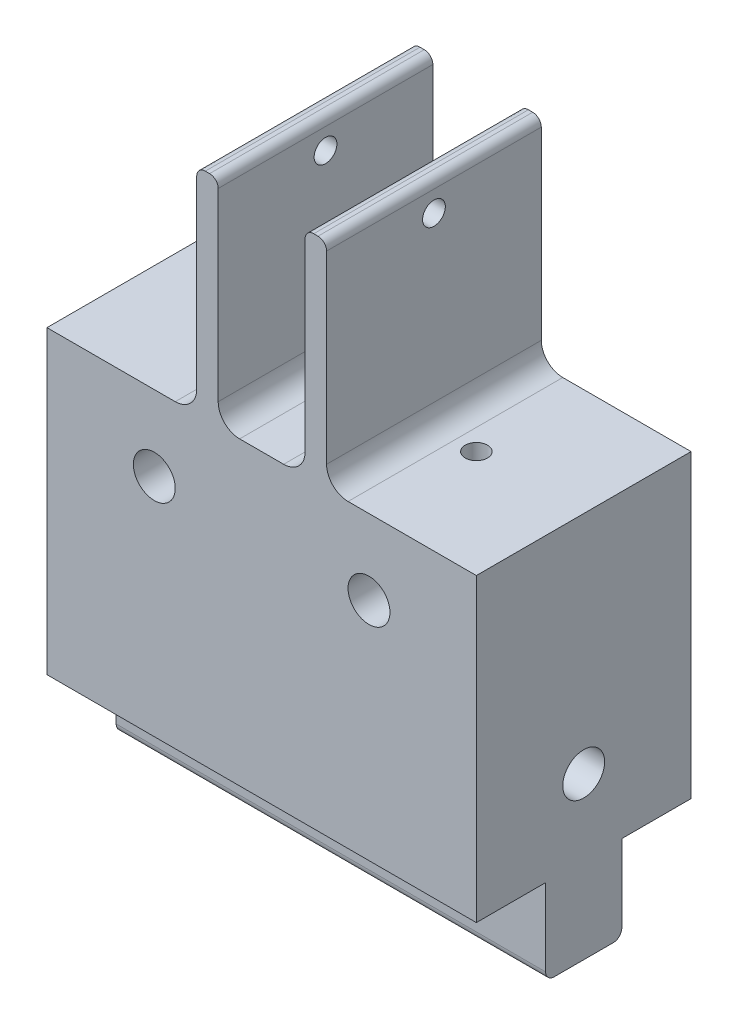
SolidWorks part; units mm, degrees
ref_plane "Front Plane" through (0, 0, 0) normal (0, 0, 1) x (1, 0, 0)
ref_plane "Top Plane" through (0, 0, 0) normal (0, 1, 0) x (1, 0, 0)
ref_plane "Right Plane" through (0, 0, 0) normal (1, 0, 0) x (0, 0, -1)
sketch "Sketch1" plane through (0, 0, 0) normal (0, 0, 1) x (1, 0, 0)
  line L1 (-50, -35) -> (50, -35)
  line L2 (-50, -35) -> (-50, 35)
  line L3 (-50, 35) -> (50, 35)
  line L4 (50, -35) -> (50, 35)
  line L5 (-50, -35) -> (50, 35) construction
  line L6 (-50, 35) -> (50, -35) construction
  point P0 (0, 0)
  dimension "D1" = 70
  dimension "D2" = 100
extrude "Boss-Extrude1" add sketch "Sketch1" along normal mid plane 50
sketch "Sketch2" plane through (0, 0, 25) normal (0, 0, 1) x (1, 0, 0)
  line L0 (0, 0) -> (50, 35) construction
  line L1 (0, 0) -> (-50, 35) construction
  circle A0 centre (25, 17.5) radius 4.875
  circle A1 centre (-25, 17.5) radius 4.875
  dimension "D1" = 9.75
extrude "Cut-Extrude1" cut sketch "Sketch2" against normal through all both and the other way through all
sketch "Sketch3" plane through (-50, 0, 0) normal (-1, 0, 0) x (0, 0, 1)
  line L0 (0, 0) -> (0, -35) construction
  line L1 (25, -35) -> (-25, -35) construction
  circle A0 centre (0, -17.5) radius 4.875
  dimension "D1" = 9.75
extrude "Cut-Extrude2" cut sketch "Sketch3" against normal through all both
sketch "Sketch4" plane through (0, 35, 0) normal (0, 1, 0) x (1, 0, 0)
  line L0 (-50, 0) -> (0, 0) construction
  line L1 (-50, -25) -> (-50, 25) construction
  line L3 (0, 0) -> (50, 0) construction
  line L4 (50, -25) -> (50, 25) construction
  circle A0 centre (-25, 0) radius 2.6
  circle A1 centre (25, 0) radius 2.6
  point P5 (-25, 0)
  dimension "D1" = 5.2
extrude "Cut-Extrude4" cut sketch "Sketch4" against normal blind 20
sketch "Sketch5" plane through (0, -35, 0) normal (0, -1, 0) x (1, 0, 0)
  line L0 (50, 25) -> (50, -25) construction
  line L1 (-50, -8.875) -> (50, -8.875)
  line L2 (-50, -8.875) -> (-50, 8.875)
  line L3 (-50, 8.875) -> (50, 8.875)
  line L4 (50, -8.875) -> (50, 8.875)
  line L5 (-50, -8.875) -> (50, 8.875) construction
  line L6 (-50, 8.875) -> (50, -8.875) construction
  point P0 (0, 0)
  dimension "D1" = 17.75
extrude "Boss-Extrude2" add sketch "Sketch5" along normal blind 20
fillet "Fillet1" radius 2 2 edges at (0, -55, -8.875) (0, -55, 8.875)
sketch "Sketch6" plane through (0, 35, 0) normal (0, 1, 0) x (1, 0, 0)
  line L0 (50, 25) -> (-50, 25) construction
  line L1 (-15.125, 25) -> (-10.125, 25)
  line L2 (-15.125, 25) -> (-15.125, -25)
  line L3 (-15.125, -25) -> (-10.125, -25)
  line L4 (-10.125, 25) -> (-10.125, -25)
  line L5 (50, -25) -> (-50, -25) construction
  line L6 (-10.125, 0) -> (10.125, 0) construction
  line L7 (15.125, 25) -> (10.125, 25)
  line L8 (15.125, 25) -> (15.125, -25)
  line L9 (15.125, -25) -> (10.125, -25)
  line L10 (10.125, 25) -> (10.125, -25)
  point P16 (0, 0)
  dimension "D1" = 20.25
  dimension "D2" = 5
extrude "Boss-Extrude3" add sketch "Sketch6" along normal blind 50
sketch "Sketch7" plane through (15.125, 0, 0) normal (1, 0, 0) x (0, 0, -1)
  line L0 (0, 85) -> (0, 78.15) construction
  line L1 (-25, 85) -> (25, 85) construction
  circle A0 centre (0, 78.15) radius 2.65
  dimension "D2" = 5.3
  dimension "D1" = 6.85
extrude "Cut-Extrude5" cut sketch "Sketch7" against normal through all both
fillet "Fillet2" radius 5 4 edges at (-15.125, 35, 0) (-10.125, 35, 0) (10.125, 35, 0) (15.125, 35, 0)
fillet "Fillet3" radius 2 4 edges at (15.125, 85, 0) (10.125, 85, 0) (-10.125, 85, 0) (-15.125, 85, 0)
